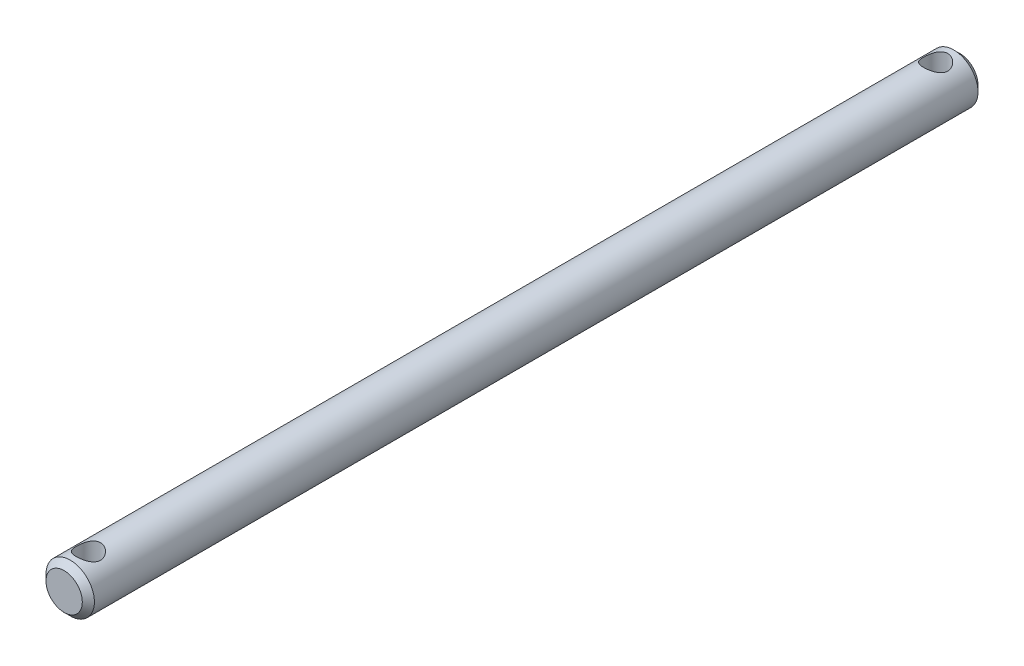
SolidWorks part; units mm, degrees
ref_plane "前基準面" through (0, 0, 0) normal (0, 0, 1) x (1, 0, 0)
ref_plane "上基準面" through (0, 0, 0) normal (0, 1, 0) x (1, 0, 0)
ref_plane "右基準面" through (0, 0, 0) normal (1, 0, 0) x (0, 0, -1)
sketch "草圖1" plane through (0, 0, 0) normal (0, 0, 1) x (1, 0, 0)
  circle A0 centre (0, 0) radius 2
  dimension "D1" = 4
extrude "填料-伸長1" add sketch "草圖1" along normal blind 74
chamfer "導角1" distance 0.5 angle 45 2 edges at (2, 0, 0) (2, 0, 74)
sketch "草圖2" plane through (0, 0, 0) normal (0, 1, 0) x (1, 0, 0)
  line L0 (2, -37) -> (6.2906, -37) construction
  line L1 (2, -73.5) -> (2, -0.5) construction
  circle A0 centre (0, -2) radius 1
  circle A1 centre (0, -72) radius 1
  dimension "D1" = 70
  dimension "D2" = 2
extrude "除料-伸長1" cut sketch "草圖2" against normal through all both and the other way through all
